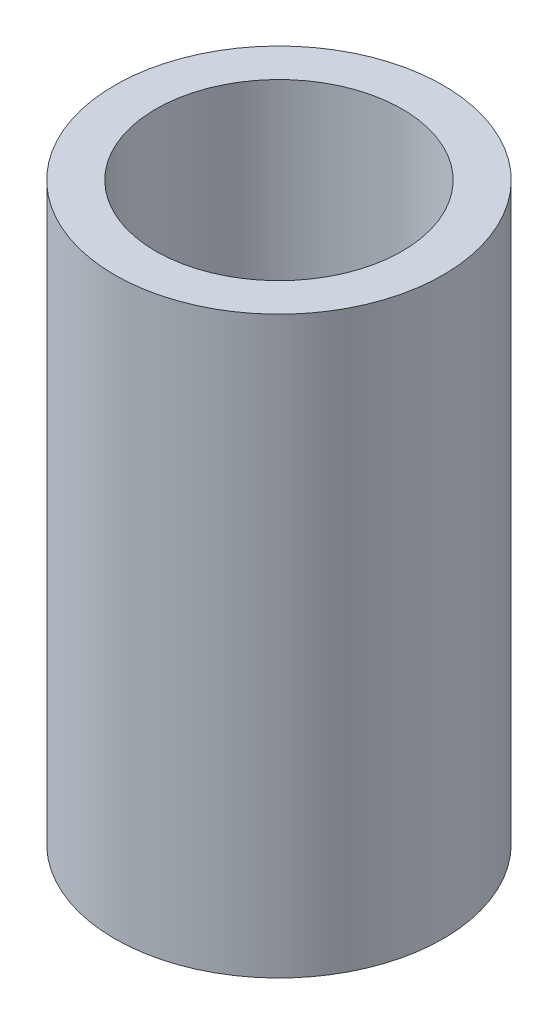
SolidWorks part; units mm, degrees
ref_plane "Front Plane" through (0, 0, 0) normal (0, 0, 1) x (1, 0, 0)
ref_plane "Top Plane" through (0, 0, 0) normal (0, 1, 0) x (1, 0, 0)
ref_plane "Right Plane" through (0, 0, 0) normal (1, 0, 0) x (0, 0, -1)
sketch "Sketch2" plane through (0, 0, 0) normal (0, 1, 0) x (1, 0, 0)
  line L0 (0, 0) -> (0, 7813.3558) construction
  line L1 (0, 0) -> (7813.3558, 0) construction
  circle A0 centre (0, 0) radius 8
  circle A1 centre (0, 0) radius 6
  dimension "D1" = 16
  dimension "D2" = 12
extrude "Boss-Extrude1" add sketch "Sketch2" along normal mid plane 28
